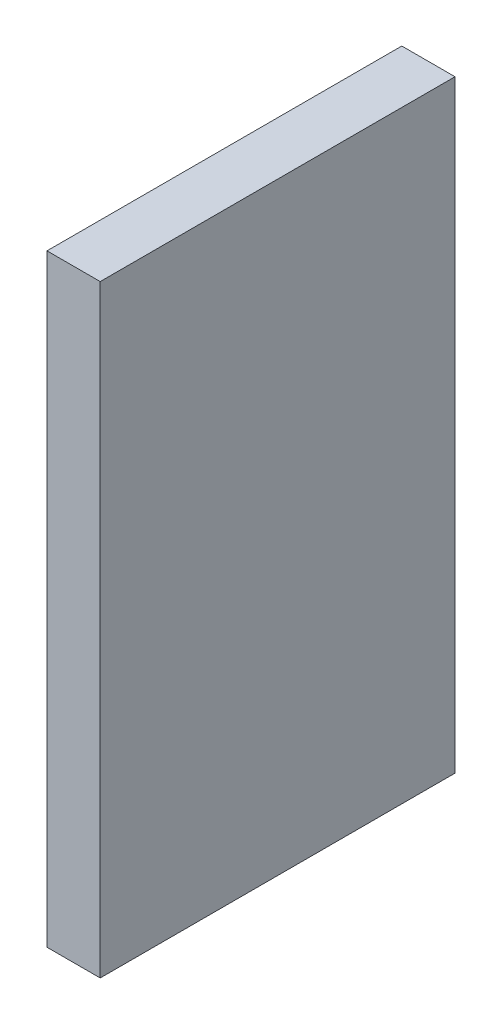
SolidWorks part; units mm, degrees
material "Balsa"
ref_plane "Plan de face" through (0, 0, 0) normal (0, 0, 1) x (1, 0, 0)
ref_plane "Plan de dessus" through (0, 0, 0) normal (0, 1, 0) x (1, 0, 0)
ref_plane "Plan de droite" through (0, 0, 0) normal (1, 0, 0) x (0, 0, -1)
sketch "Esquisse1" plane through (0, 0, 0) normal (0, 1, 0) x (1, 0, 0)
  line L1 (-36.4742, -41.2356) -> (-21.4742, -41.2356)
  line L2 (-36.4742, -41.2356) -> (-36.4742, 58.7644)
  line L3 (-36.4742, 58.7644) -> (-21.4742, 58.7644)
  line L4 (-21.4742, -41.2356) -> (-21.4742, 58.7644)
  dimension "D1" = 100
  dimension "D2" = 15
extrude "Boss.-Extru.1" add sketch "Esquisse1" along normal blind 170
